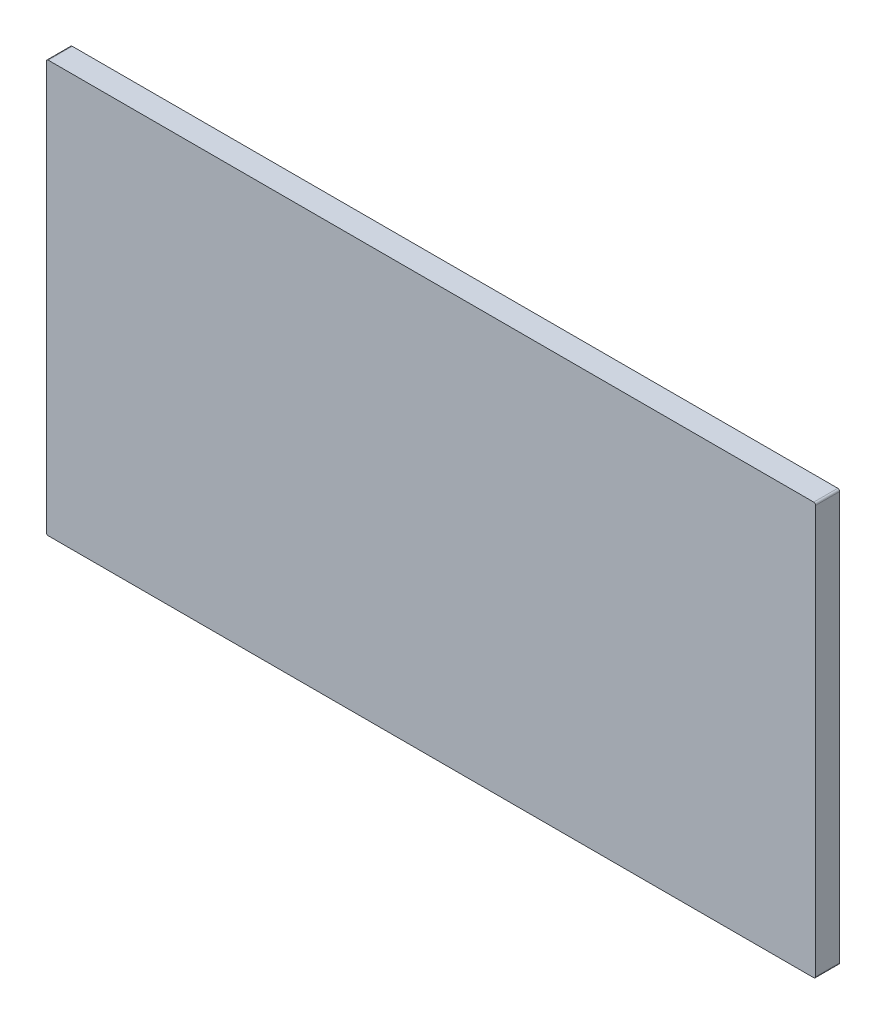
SolidWorks part; units mm, degrees
ref_plane "Front Plane" through (0, 0, 0) normal (0, 0, 1) x (1, 0, 0)
ref_plane "Top Plane" through (0, 0, 0) normal (0, 1, 0) x (1, 0, 0)
ref_plane "Right Plane" through (0, 0, 0) normal (1, 0, 0) x (0, 0, -1)
sketch "Sketch1" plane through (0, 0, 0) normal (0, 0, 1) x (1, 0, 0)
  line L1 (304.8, -163.195) -> (-304.8, -163.195)
  line L2 (304.8, -163.195) -> (304.8, 163.195)
  line L3 (304.8, 163.195) -> (-304.8, 163.195)
  line L4 (-304.8, -163.195) -> (-304.8, 163.195)
  line L5 (304.8, -163.195) -> (-304.8, 163.195) construction
  line L6 (304.8, 163.195) -> (-304.8, -163.195) construction
  point P0 (0, 0)
  dimension "D1" = 326.39
  dimension "D2" = 609.6
extrude "Boss-Extrude1" add sketch "Sketch1" along normal mid plane 19.05
sketch "Sketch2" [suppressed] plane through (0, 0, 9.525) normal (0, 0, 1) x (1, 0, 0)
  line L0 (292.1, 397.75) -> (292.1, 110.25) construction
  line L1 (198.85, 397.75) -> (385.35, 397.75)
  line L2 (198.85, 397.75) -> (198.85, 110.25)
  line L3 (198.85, 110.25) -> (385.35, 110.25)
  line L4 (385.35, 397.75) -> (385.35, 110.25)
  line L5 (140.85, 70.95) -> (443.35, 70.95)
  line L6 (140.85, 70.95) -> (140.85, -426.55)
  line L7 (140.85, -426.55) -> (443.35, -426.55)
  line L8 (443.35, 70.95) -> (443.35, -426.55)
  line L9 (-379.73, 444.5) -> (90.17, 444.5)
  line L10 (-379.73, 444.5) -> (-379.73, -241.3)
  line L11 (-379.73, -241.3) -> (90.17, -241.3)
  line L12 (90.17, 444.5) -> (90.17, -241.3)
  line L13 (198.85, 254) -> (385.35, 254) construction
  line L14 (292.1, 70.95) -> (292.1, -426.55) construction
  line L15 (140.85, -177.8) -> (443.35, -177.8) construction
  line L16 (-144.78, 444.5) -> (-144.78, -241.3) construction
  line L17 (-379.73, 101.6) -> (90.17, 101.6) construction
  line L18 (-144.78, -279.4) -> (-144.78, -241.3) construction
  line L19 (-379.73, -279.4) -> (90.17, -279.4)
  line L20 (-379.73, -279.4) -> (-379.73, -457.2)
  line L21 (-379.73, -457.2) -> (90.17, -457.2)
  line L22 (90.17, -279.4) -> (90.17, -457.2)
  line L23 (-379.73, -368.3) -> (90.17, -368.3) construction
  line L24 (-476.25, 476.25) -> (-476.25, -476.25) construction
  dimension "D1" = 292.1
  dimension "D2" = 302.5
  dimension "D3" = 96.52
  dimension "D4" = 186.5
  dimension "D5" = 497.5
  dimension "D6" = 177.8
  dimension "D7" = 254
  dimension "D8" = 287.5
  dimension "D9" = 685.8
  dimension "D10" = 101.6
  dimension "D11" = 469.9
  dimension "D13" = 177.8
  dimension "D14" = 368.3
extrude "Cut-Extrude1" [suppressed] cut sketch "Sketch2" against normal through all
fillet "Fillet1" [suppressed] radius 1.5
fillet "Fillet2" radius 1.5 4 edges at (-304.8, -163.195, 0) (304.8, -163.195, 0) (304.8, 163.195, 0) (-304.8, 163.195, 0)
